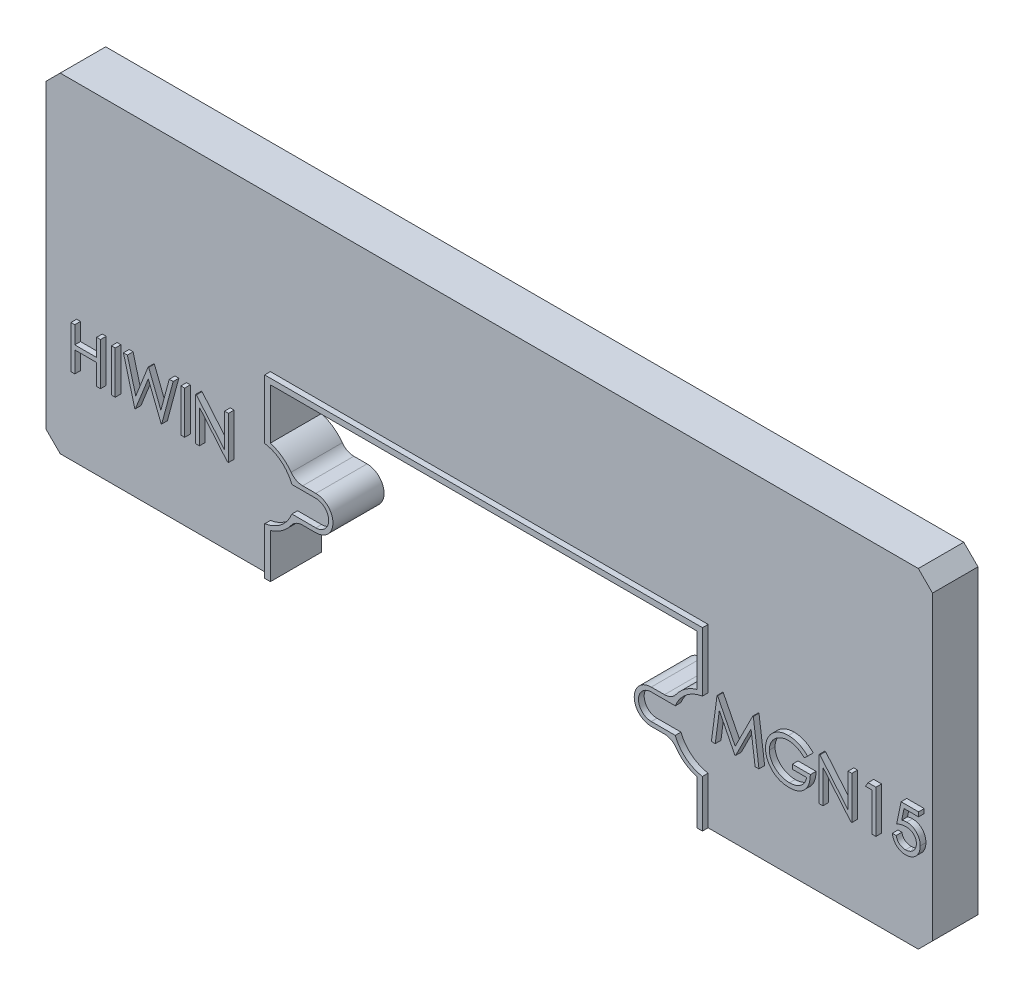
SolidWorks part; units mm, degrees
material "ABS"
ref_plane "Front Plane" through (0, 0, 0) normal (0, 0, 1) x (1, 0, 0)
ref_plane "Top Plane" through (0, 0, 0) normal (0, 1, 0) x (1, 0, 0)
ref_plane "Right Plane" through (0, 0, 0) normal (1, 0, 0) x (0, 0, -1)
sketch "Sketch1" plane through (0, 0, 0) normal (0, 0, 1) x (1, 0, 0)
  line L0 (0, 5.8) -> (0, -5.8) construction
  line L1 (-7.5, -5.8) -> (-15.095, -5.8)
  line L2 (-15.095, -5.8) -> (-15.595, -5.3)
  line L3 (-15.595, -5.3) -> (-15.595, 5.3)
  line L4 (-15.595, 5.3) -> (-15.095, 5.8)
  line L5 (-15.095, 5.8) -> (15.095, 5.8)
  line L6 (-7.5, -5.8) -> (-7.5, -4.2402)
  line L7 (7.5018, 0.2) -> (-7.5018, 0.2)
  line L8 (-7.5018, 0.2) -> (-7.5018, -1.5793)
  line L9 (-5.9, -3.51) -> (-6.6473, -3.51)
  line L10 (-5.9, -2.31) -> (-6.6473, -2.31)
  line L11 (15.595, 5.3) -> (15.095, 5.8)
  line L12 (15.595, -5.3) -> (15.595, 5.3)
  line L13 (15.095, -5.8) -> (15.595, -5.3)
  line L14 (7.5, -5.8) -> (15.095, -5.8)
  line L15 (7.5, -5.8) -> (7.5, -4.2402)
  line L16 (5.9, -3.51) -> (6.6473, -3.51)
  line L17 (5.9, -2.31) -> (6.6473, -2.31)
  line L18 (7.5018, 0.2) -> (7.5018, -1.5793)
  circle A0 centre (-7.9, -2.91) radius 1.389 construction
  circle A1 centre (-5.9, -2.91) radius 0.6 construction
  arc A2 (-7.5, -4.2402) -> (-6.6473, -3.51) centre (-7.9, -2.91) ccw
  arc A3 (-6.6473, -2.31) -> (-7.5018, -1.5793) centre (-7.9, -2.91) ccw
  arc A4 (-5.9, -3.51) -> (-5.9, -2.31) centre (-5.9, -2.91) ccw
  arc A5 (7.5, -4.2402) -> (6.6473, -3.51) centre (7.9, -2.91) cw
  arc A6 (5.9, -3.51) -> (5.9, -2.31) centre (5.9, -2.91) cw
  arc A7 (6.6473, -2.31) -> (7.5018, -1.5793) centre (7.9, -2.91) cw
  point P4 (0, 0)
  point P39 (0, 0.2)
  dimension "D8" = 2.778
  dimension "D9" = 1.2
  dimension "D10" = 2.89
  dimension "D11" = 2.89
  dimension "D12" = 5.9
  dimension "D13" = 7.9
  dimension "D1" = 11.6
  dimension "D2" = 0.5
  dimension "D3" = 0.5
  dimension "D4" = 0.5
  dimension "D5" = 0.5
  dimension "D6" = 15.595
  dimension "D7" = 7.5
  dimension "D14" = 7.5018
  dimension "D15" = 6
extrude "Boss-Extrude1" add sketch "Sketch1" against normal blind 1.6 contours A7 L17 A6 L16 A5 L15 L14 L13 L12 L11 L5 L4 L3 L2 L1 L6 A2 L9 A4 L10 A3 L8 L7 L18
fillet "Fillet1" radius 0.5 4 edges at (6.6473, -2.31, -0.8) (6.6473, -3.51, -0.8) (-6.6473, -3.51, -0.8) (-6.6473, -2.31, -0.8)
sketch "Sketch2" plane through (0, 0, 0) normal (0, 0, 1) x (1, 0, 0)
  line L0 (-7.5, -5.8) -> (-7.7, -5.8)
  line L1 (-7.5, -5.8) -> (-15.095, -5.8) construction
  line L2 (-7.7, -5.8) -> (-7.7, -4.1338)
  line L3 (-7.5, -5.8) -> (-7.5, -4.2402) construction
  line L4 (-7.7018, 0.4) -> (-7.7018, -1.6859)
  line L5 (-7.5018, 0.2) -> (-7.5018, -1.5793) construction
  line L6 (-7.7018, 0.4) -> (7.7018, 0.4)
  line L7 (7.5018, 0.2) -> (-7.5018, 0.2) construction
  line L8 (-7.5, -5.8) -> (-7.5, -4.2402)
  line L9 (-6.3643, -3.51) -> (-5.9, -3.51)
  line L10 (-5.9, -2.31) -> (-6.3643, -2.31)
  line L11 (-7.5018, -1.5793) -> (-7.5018, 0.2)
  line L12 (-7.5018, 0.2) -> (7.5018, 0.2)
  line L13 (0, 0.2) -> (0, -5.8007) construction
  line L14 (-5.9, -3.36) -> (-6.7445, -3.36)
  line L15 (-5.9, -2.46) -> (-6.7445, -2.46)
  line L16 (7.5018, -1.5793) -> (7.5018, 0.2)
  line L17 (7.7018, 0.4) -> (7.7018, -1.6859)
  line L18 (5.9, -2.46) -> (6.7445, -2.46)
  line L19 (5.9, -2.31) -> (6.3643, -2.31)
  line L20 (6.3643, -3.51) -> (5.9, -3.51)
  line L21 (5.9, -3.36) -> (6.7445, -3.36)
  line L22 (7.5, -5.8) -> (7.5, -4.2402)
  line L23 (7.7, -5.8) -> (7.7, -4.1338)
  line L24 (7.5, -5.8) -> (7.7, -5.8)
  circle A0 centre (-7.9, -2.91) radius 1.24 construction
  circle A1 centre (-5.9, -2.91) radius 0.45 construction
  arc A2 (-7.5, -4.2402) -> (-6.7708, -3.7188) centre (-7.9, -2.91) ccw
  arc A3 (-7.5, -4.2402) -> (-6.7708, -3.7188) centre (-7.9, -2.91) ccw construction
  arc A4 (-5.9, -3.51) -> (-5.9, -2.31) centre (-5.9, -2.91) ccw
  arc A5 (-5.9, -3.51) -> (-5.9, -2.31) centre (-5.9, -2.91) ccw construction
  arc A6 (-6.3643, -3.51) -> (-6.7708, -3.7188) centre (-6.3643, -4.01) ccw
  arc A7 (-6.3643, -3.51) -> (-6.7708, -3.7188) centre (-6.3643, -4.01) ccw construction
  arc A8 (-6.7708, -2.1012) -> (-6.3643, -2.31) centre (-6.3643, -1.81) ccw
  arc A9 (-6.7708, -2.1012) -> (-6.3643, -2.31) centre (-6.3643, -1.81) ccw construction
  arc A10 (-6.7708, -2.1012) -> (-7.5018, -1.5793) centre (-7.9, -2.91) ccw
  arc A11 (-7.7, -4.1338) -> (-6.7445, -3.36) centre (-7.9, -2.91) ccw
  arc A12 (-6.7445, -2.46) -> (-7.7018, -1.6859) centre (-7.9, -2.91) ccw
  arc A13 (-5.9, -3.36) -> (-5.9, -2.46) centre (-5.9, -2.91) ccw
  arc A14 (6.7708, -2.1012) -> (7.5018, -1.5793) centre (7.9, -2.91) cw
  arc A15 (6.7445, -2.46) -> (7.7018, -1.6859) centre (7.9, -2.91) cw
  arc A16 (6.7708, -2.1012) -> (6.3643, -2.31) centre (6.3643, -1.81) cw
  arc A17 (5.9, -3.36) -> (5.9, -2.46) centre (5.9, -2.91) cw
  arc A18 (5.9, -3.51) -> (5.9, -2.31) centre (5.9, -2.91) cw
  arc A19 (6.3643, -3.51) -> (6.7708, -3.7188) centre (6.3643, -4.01) cw
  arc A20 (7.5, -4.2402) -> (6.7708, -3.7188) centre (7.9, -2.91) cw
  arc A21 (7.7, -4.1338) -> (6.7445, -3.36) centre (7.9, -2.91) cw
  point P63 (0, 0.4)
  dimension "D1" = 2.48
  dimension "D2" = 0.9
  dimension "D5" = 0.2
  dimension "D3" = 0.2
  dimension "D4" = 0.2
extrude "Boss-Extrude3" add sketch "Sketch2" along normal blind 0.2
sketch "Sketch3" plane through (0, 0, 0) normal (0, 0, 1) x (1, 0, 0)
  line L0 (-7.9, -2.91) -> (-15.595, -2.91) construction
  line L1 (-15.595, -5.3) -> (-15.595, 5.3) construction
  line L2 (7.9, -2.91) -> (15.595, -2.91) construction
  line L3 (15.595, -5.3) -> (15.595, 5.3) construction
  text T0 "HIWIN" font "Century Gothic" height 1.5
  text T1 "MGN15" font "Century Gothic" height 1.5
extrude "Boss-Extrude4" add sketch "Sketch3" along normal blind 0.2
